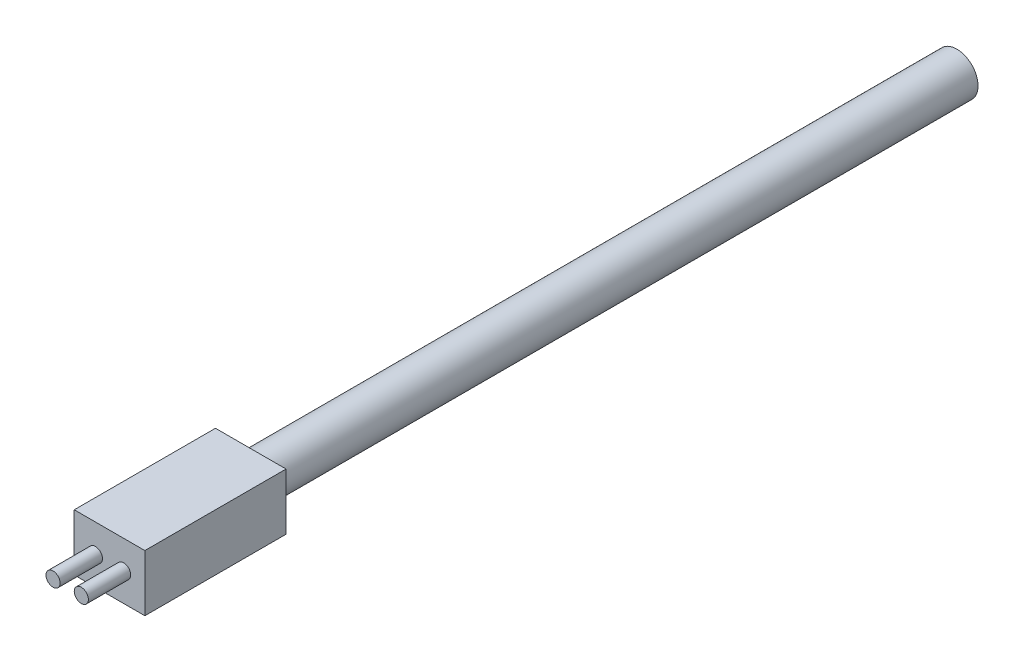
SolidWorks part; units mm, degrees
ref_plane "Front Plane" through (0, 0, 0) normal (0, 0, 1) x (1, 0, 0)
ref_plane "Top Plane" through (0, 0, 0) normal (0, 1, 0) x (1, 0, 0)
ref_plane "Right Plane" through (0, 0, 0) normal (1, 0, 0) x (0, 0, -1)
sketch "Sketch2" plane through (0, 0, 0) normal (0, 1, 0) x (1, 0, 0)
  line L1 (-2.5, 5) -> (2.5, 5)
  line L2 (-2.5, 5) -> (-2.5, -5)
  line L3 (-2.5, -5) -> (2.5, -5)
  line L4 (2.5, 5) -> (2.5, -5)
  line L5 (-2.5, 5) -> (2.5, -5) construction
  line L6 (-2.5, -5) -> (2.5, 5) construction
  point P0 (0, 0)
  point P5 (0, 0)
  dimension "D1" = 10
  dimension "D2" = 5
extrude "Boss-Extrude1" add sketch "Sketch2" along normal blind 4
sketch "Sketch4" plane through (0, 0, 5) normal (0, 0, 1) x (1, 0, 0)
  line L0 (-1, 2) -> (1, 2) construction
  line L1 (-2.5, 0) -> (2.5, 0) construction
  circle A0 centre (-1, 2) radius 0.5
  circle A1 centre (1, 2) radius 0.5
  point P4 (1.3632, 1.7282)
  point P5 (0, 2)
  point P8 (0, 0)
  dimension "D1" = 1
  dimension "D2" = 1
  dimension "D3" = 2
  dimension "D4" = 2
extrude "Boss-Extrude2" add sketch "Sketch4" along normal blind 3
sketch "Sketch5" plane through (0, 0, -5) normal (0, 0, -1) x (-1, 0, 0)
  line L0 (-2.5, 2) -> (2.5, 2) construction
  line L1 (-2.5, 4) -> (-2.5, 0) construction
  line L2 (2.5, 4) -> (2.5, 0) construction
  circle A0 centre (0, 2) radius 1.5
  point P8 (0, 2)
  dimension "D1" = 3
extrude "Boss-Extrude3" add sketch "Sketch5" along normal blind 50
